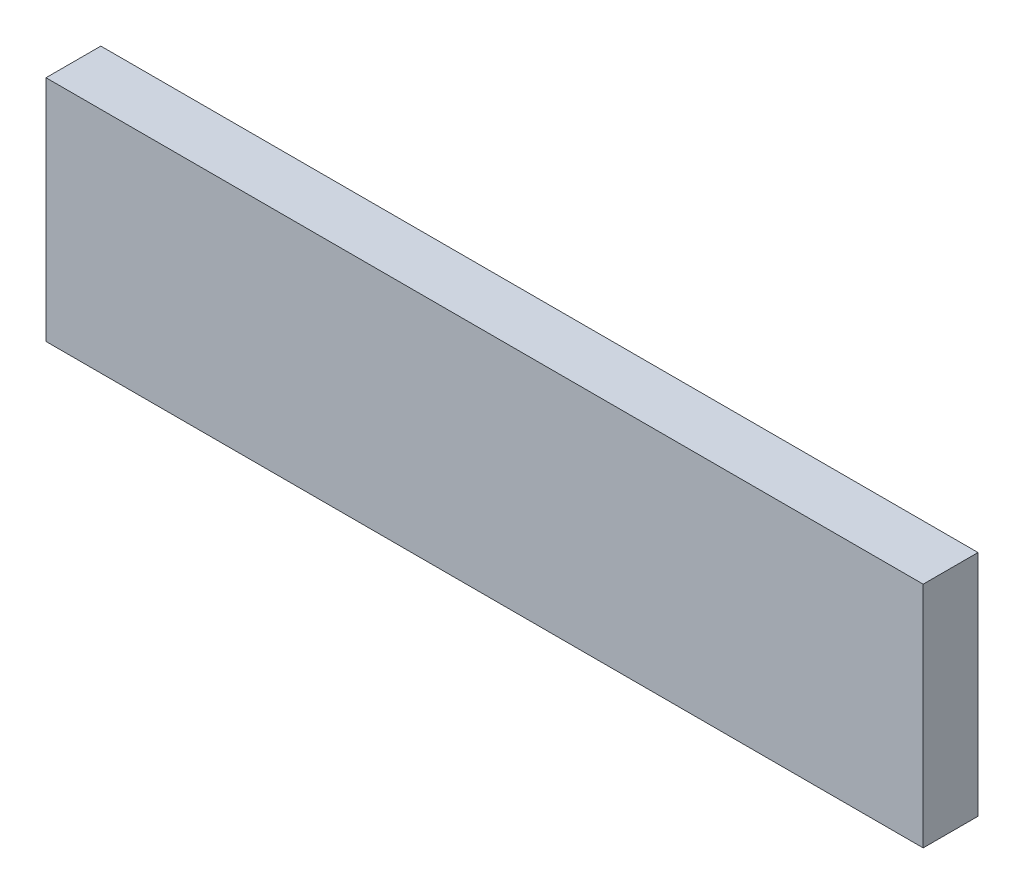
SolidWorks part; units mm, degrees
ref_plane "Plano frontal" through (0, 0, 0) normal (0, 0, 1) x (1, 0, 0)
ref_plane "Plano superior" through (0, 0, 0) normal (0, 1, 0) x (1, 0, 0)
ref_plane "Plano direito" through (0, 0, 0) normal (1, 0, 0) x (0, 0, -1)
sketch "Esboço1" plane through (0, 0, 0) normal (0, 0, 1) x (1, 0, 0)
  line L1 (-96, 25) -> (96, 25)
  line L2 (-96, 25) -> (-96, -25)
  line L3 (-96, -25) -> (96, -25)
  line L4 (96, 25) -> (96, -25)
  line L5 (-96, 25) -> (96, -25) construction
  line L6 (-96, -25) -> (96, 25) construction
  point P0 (0, 0)
extrude "Ressalto-extrusão1" add sketch "Esboço1" along normal mid plane 12
ref_plane "Plano1" through (0, -25, 0) normal (0, -1, 0) x (-1, 0, 0)
sketch "Esboço2" plane through (0, -25, 0) normal (0, -1, 0) x (-1, 0, 0)
  circle A0 centre (77.5, 0) radius 1.5
  circle A1 centre (-77.5, 0) radius 1.5
extrude "Corte-extrusão1" cut sketch "Esboço2" against normal mid plane 30
